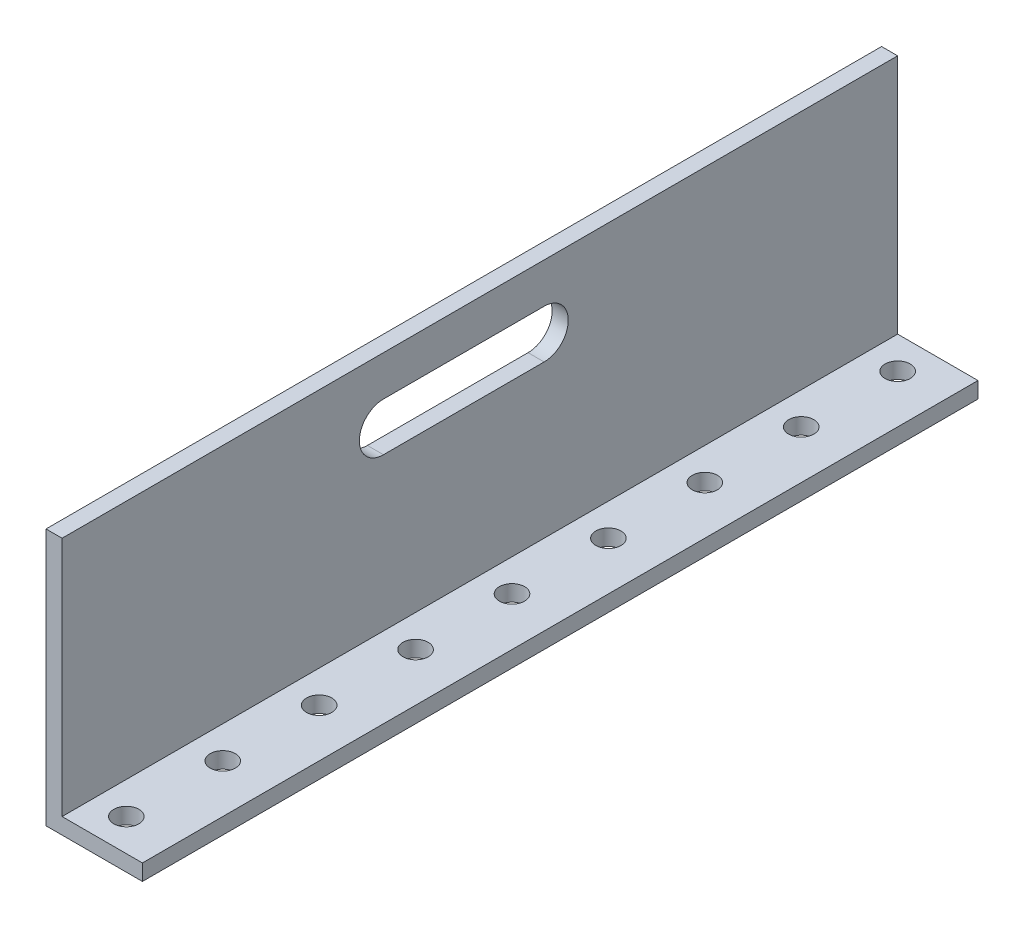
SolidWorks part; units mm, degrees
material "6061-T6 (SS)"
ref_plane "Front Plane" through (0, 0, 0) normal (0, 0, 1) x (1, 0, 0)
ref_plane "Top Plane" through (0, 0, 0) normal (0, 1, 0) x (1, 0, 0)
ref_plane "Right Plane" through (0, 0, 0) normal (1, 0, 0) x (0, 0, -1)
sketch "Sketch3" plane through (0, 0, 0) normal (0, 0, 1) x (1, 0, 0)
  line L1 (0, 0) -> (3.175, 0)
  line L2 (0, 0) -> (0, 50.8)
  line L3 (0, 50.8) -> (3.175, 50.8)
  line L4 (3.175, 0) -> (3.175, 50.8)
  line L5 (0, 0) -> (19.05, 0)
  line L6 (0, 0) -> (0, 3.175)
  line L7 (0, 3.175) -> (19.05, 3.175)
  line L8 (19.05, 0) -> (19.05, 3.175)
  dimension "D1" = 19.05
  dimension "D2" = 50.8
  dimension "D3" = 3.175
  dimension "D4" = 3.175
extrude "Boss-Extrude1" add sketch "Sketch3" along normal blind 165.1 contours L2 L7 L4 L3 | L7 L2 L1 L4 | L5 L8 L7 L4
sketch "Sketch4" plane through (0, 3.175, 0) normal (0, 1, 0) x (1, 0, 0)
  line L0 (3.175, -165.1) -> (3.175, 0) construction
  line L1 (3.175, 0) -> (19.05, 0) construction
  circle A0 centre (9.525, -6.35) radius 2.4892
  circle A1 centre (9.525, -25.4) radius 2.4892
  circle A2 centre (9.525, -44.45) radius 2.4892
  circle A3 centre (9.525, -63.5) radius 2.4892
  circle A4 centre (9.525, -82.55) radius 2.4892
  circle A5 centre (9.525, -101.6) radius 2.4892
  circle A6 centre (9.525, -120.65) radius 2.4892
  circle A7 centre (9.525, -139.7) radius 2.4892
  circle A8 centre (9.525, -158.75) radius 2.4892
  dimension "D1" = 4.9784
  dimension "D2" = 6.35
  dimension "D3" = 6.35
  dimension "D5" = 19.05
  dimension "D4" = 9
extrude "Cut-Extrude1" cut sketch "Sketch4" against normal blind 165.1
sketch "Sketch5" plane through (0, 0, 0) normal (-1, 0, 0) x (0, 0, 1)
  line L0 (69.85, 38.1) -> (101.6, 38.1) construction
  line L1 (69.85, 42.8625) -> (101.6, 42.8625)
  line L2 (69.85, 33.3375) -> (101.6, 33.3375)
  line L4 (165.1, 50.8) -> (0, 50.8) construction
  line L5 (165.1, 0) -> (165.1, 50.8) construction
  arc A0 (69.85, 42.8625) -> (69.85, 33.3375) centre (69.85, 38.1) ccw
  arc A1 (101.6, 33.3375) -> (101.6, 42.8625) centre (101.6, 38.1) ccw
  point P2 (85.725, 38.1)
  dimension "D3" = 4.7625
  dimension "D1" = 63.5
  dimension "D2" = 12.7
  dimension "D4" = 31.75
extrude "Cut-Extrude2" cut sketch "Sketch5" against normal blind 165.1
